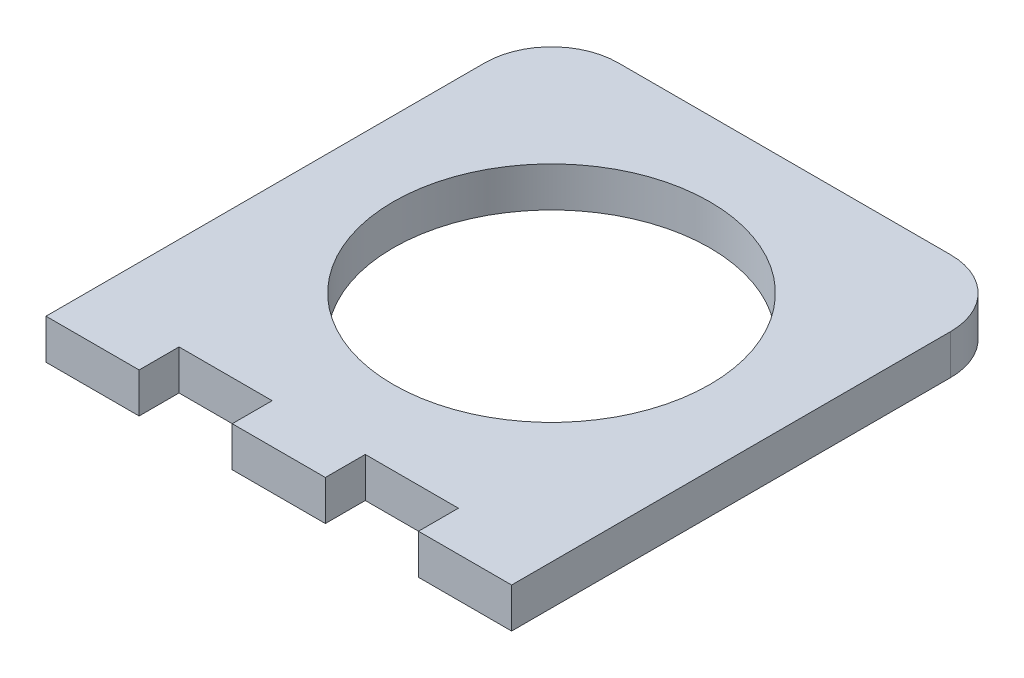
SolidWorks part; units mm, degrees
ref_plane "Front Plane" through (0, 0, 0) normal (0, 0, 1) x (1, 0, 0)
ref_plane "Top Plane" through (0, 0, 0) normal (0, 1, 0) x (1, 0, 0)
ref_plane "Right Plane" through (0, 0, 0) normal (1, 0, 0) x (0, 0, -1)
sketch "Sketch2" plane through (0, 0, 0) normal (0, 1, 0) x (1, 0, 0)
  line L1 (17.5, -19) -> (-17.5, -19)
  line L2 (17.5, -19) -> (17.5, 19)
  line L3 (17.5, 19) -> (-17.5, 19)
  line L4 (-17.5, -19) -> (-17.5, 19)
  line L5 (17.5, -19) -> (-17.5, 19) construction
  line L6 (17.5, 19) -> (-17.5, -19) construction
  point P0 (0, 0)
  dimension "D1" = 35
  dimension "D2" = 38
extrude "Boss-Extrude1" add sketch "Sketch2" along normal blind 3
sketch "Sketch3" plane through (0, 3, 0) normal (0, 1, 0) x (1, 0, 0)
  line L0 (17.5, 19) -> (-17.5, 19) construction
  circle A0 centre (0, 1.5) radius 11.9
  dimension "D1" = 23.8
  dimension "D2" = 17.5
extrude "Cut-Extrude1" cut sketch "Sketch3" against normal blind 3 contours A0
fillet "Fillet1" radius 5 1 edges at (17.5, 1.5, -19)
fillet "Fillet2" radius 5 1 edges at (-17.5, 1.5, -19)
sketch "Sketch4" plane through (0, 3, 0) normal (0, 1, 0) x (1, 0, 0)
  line L0 (17.5, -19) -> (-17.5, -19) construction
  line L1 (-10.5, -19) -> (-3.5, -19)
  line L2 (-10.5, -19) -> (-10.5, -16)
  line L3 (-10.5, -16) -> (-3.5, -16)
  line L4 (-3.5, -19) -> (-3.5, -16)
  line L5 (-17.5, -19) -> (-17.5, 14) construction
  dimension "D1" = 7
  dimension "D2" = 3
  dimension "D3" = 7
extrude "Cut-Extrude2" cut sketch "Sketch4" against normal blind 3
pattern_linear "LPattern1" count 2 spacing 14 along (1, 0, 0) of "Cut-Extrude2"
